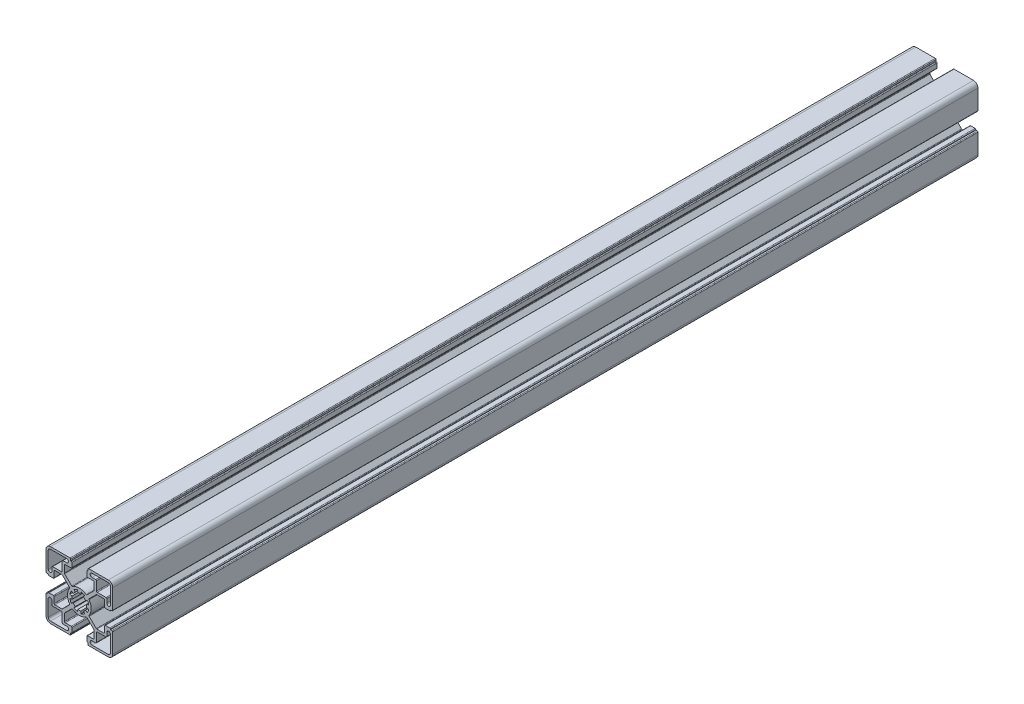
SolidWorks part; units mm, degrees
material "6063-O"
ref_plane "Front Plane" through (0, 0, 0) normal (0, 0, 1) x (1, 0, 0)
ref_plane "Top Plane" through (0, 0, 0) normal (0, 1, 0) x (1, 0, 0)
ref_plane "Right Plane" through (0, 0, 0) normal (1, 0, 0) x (0, 0, -1)
sketch "Sketch1" plane through (0, 0, 0) normal (0, 0, 1) x (1, 0, 0)
  line L0 (0, 22.5) -> (0, -22.5) construction
  line L1 (22.5, 0) -> (-22.5, 0) construction
  line L2 (-5.8, 22.5) -> (5.8, 22.5) construction
  line L3 (-5, 21) -> (5, 21) construction
  line L4 (-10.05, 10.05) -> (10.05, 10.05) construction
  line L5 (0, 0) -> (-10.05, 10.05) construction
  circle A0 centre (0, 0) radius 5 construction
  point P4 (0, 0)
  point P8 (0, 0)
  point P10 (0, 8)
  point P14 (0, 22.5)
  point P17 (0, 21)
  point P19 (0, 10.05)
sketch "Sketch2" plane through (0, 0, 0) normal (1, 0, 0) x (0, 0, -1)
  line L0 (152.4, 0) -> (-152.4, 0) construction
  point P4 (0, 0)
  dimension "D1" = 304.8
sketch "Sketch3" plane through (0, 0, 0) normal (0, 0, 1) x (1, 0, 0)
  line L5 (-21, 8.5375) -> (-21, 19.5)
  line L9 (0, 0) -> (-22.5, 22.5) construction
  line L10 (-11.55, -10.05) -> (-6.3569, -4.8569)
  line L11 (-19.5, 21) -> (-8.5375, 21)
  line L38 (-5.8, 22.5) -> (-5.8, 21)
  line L46 (-5.8, 21) -> (-5, 21)
  line L62 (-5, 21) -> (-5, 17.025)
  line L74 (-5, 17.025) -> (-10.05, 17.025)
  line L76 (-10.05, 17.025) -> (-10.05, 11.55)
  line L77 (-10.05, 11.55) -> (-4.8569, 6.3569)
  line L78 (-18.525, 8.5375) -> (-18.525, 11.55)
  line L79 (-10.05, 17.025) -> (-10.05, 22.5) construction
  line L80 (0, 22.5) -> (0, -22.5) construction
  line L81 (-5.8, 22.5) -> (5.8, 22.5) construction
  line L82 (10.05, 11.55) -> (4.8569, 6.3569)
  line L83 (10.05, 17.025) -> (10.05, 11.55)
  line L84 (5, 17.025) -> (10.05, 17.025)
  line L85 (5, 21) -> (5, 17.025)
  line L86 (5.8, 21) -> (5, 21)
  line L87 (5.8, 22.5) -> (5.8, 21)
  line L88 (-22.5, -5.8) -> (-21, -5.8)
  line L89 (-21, -5.8) -> (-21, -5)
  line L90 (-21, -5) -> (-17.025, -5)
  line L91 (-17.025, -5) -> (-17.025, -10.05)
  line L92 (-17.025, -10.05) -> (-11.55, -10.05)
  line L93 (-11.55, -10.05) -> (-6.3569, -4.8569)
  line L94 (-11.55, 10.05) -> (-6.3569, 4.8569)
  line L95 (-17.025, 10.05) -> (-11.55, 10.05)
  line L96 (-17.025, 5) -> (-17.025, 10.05)
  line L97 (-21, 5) -> (-17.025, 5)
  line L98 (-21, 5.8) -> (-21, 5)
  line L99 (-22.5, 5.8) -> (-21, 5.8)
  line L100 (-22.5, 5.8) -> (-22.5, 19.5)
  line L101 (-19.5, 22.5) -> (-5.8, 22.5)
  line L102 (-18.525, 11.55) -> (-11.55, 11.55)
  line L103 (-8.5375, 18.525) -> (-11.55, 18.525)
  line L104 (-11.55, 18.525) -> (-11.55, 11.55)
  line L108 (5.8, -22.5) -> (5.8, -21)
  line L113 (5.8, -21) -> (5, -21)
  line L117 (5.8, 22.5) -> (19.5, 22.5)
  line L118 (22.5, 19.5) -> (22.5, 5.8)
  line L119 (19.5, -22.5) -> (5.8, -22.5)
  line L120 (0, 0) -> (22.5, 0) construction
  line L121 (-22.5, -19.5) -> (-22.5, -5.8)
  line L136 (5, -21) -> (5, -17.025)
  line L137 (5, -17.025) -> (10.05, -17.025)
  line L138 (10.05, -17.025) -> (10.05, -11.55)
  line L139 (10.05, -11.55) -> (4.8569, -6.3569)
  line L140 (-10.05, -11.55) -> (-4.8569, -6.3569)
  line L141 (-10.05, -17.025) -> (-10.05, -11.55)
  line L142 (-5, -17.025) -> (-10.05, -17.025)
  line L143 (-5, -21) -> (-5, -17.025)
  line L144 (-5.8, -21) -> (-5, -21)
  line L145 (-5.8, -22.5) -> (-5.8, -21)
  line L146 (-5.8, -22.5) -> (-19.5, -22.5)
  line L147 (22.5, 5.8) -> (21, 5.8)
  line L148 (21, 5.8) -> (21, 5)
  line L149 (21, 5) -> (17.025, 5)
  line L150 (17.025, 5) -> (17.025, 10.05)
  line L151 (17.025, 10.05) -> (11.55, 10.05)
  line L152 (11.55, 10.05) -> (6.3569, 4.8569)
  line L153 (11.55, -10.05) -> (6.3569, -4.8569)
  line L154 (17.025, -10.05) -> (11.55, -10.05)
  line L155 (17.025, -5) -> (17.025, -10.05)
  line L156 (21, -5) -> (17.025, -5)
  line L157 (21, -5.8) -> (21, -5)
  line L158 (22.5, -5.8) -> (21, -5.8)
  line L159 (11.55, -10.05) -> (6.3569, -4.8569)
  line L160 (22.5, -5.8) -> (22.5, -19.5)
  line L161 (8.5375, 21) -> (19.5, 21)
  line L162 (21, 19.5) -> (21, 8.5375)
  line L163 (8.5375, 18.525) -> (11.55, 18.525)
  line L164 (11.55, 18.525) -> (11.55, 11.55)
  line L165 (18.525, 8.5375) -> (18.525, 11.55)
  line L166 (18.525, 11.55) -> (11.55, 11.55)
  line L167 (21, -8.5375) -> (21, -19.5)
  line L168 (19.5, -21) -> (8.5375, -21)
  line L169 (18.525, -8.5375) -> (18.525, -11.55)
  line L170 (18.525, -11.55) -> (11.55, -11.55)
  line L171 (8.5375, -18.525) -> (11.55, -18.525)
  line L172 (11.55, -18.525) -> (11.55, -11.55)
  line L173 (-8.5375, -21) -> (-19.5, -21)
  line L174 (-21, -19.5) -> (-21, -8.5375)
  line L175 (-8.5375, -18.525) -> (-11.55, -18.525)
  line L176 (-11.55, -18.525) -> (-11.55, -11.55)
  line L177 (-18.525, -8.5375) -> (-18.525, -11.55)
  line L178 (-18.525, -11.55) -> (-11.55, -11.55)
  line L179 (0, 0) -> (-11.55, 11.55) construction
  line L180 (0, 0) -> (11.55, 11.55) construction
  arc A2 (-21, 19.5) -> (-19.5, 21) centre (-19.5, 19.5) cw
  arc A73 (-4.8569, 6.3569) -> (4.8569, 6.3569) centre (0, 0) cw
  arc A74 (-6.3569, 4.8569) -> (-6.3569, -4.8569) centre (0, 0) ccw
  arc A75 (-19.5, 22.5) -> (-22.5, 19.5) centre (-19.5, 19.5) ccw
  arc A76 (-21, 8.5375) -> (-18.525, 8.5375) centre (-19.7625, 8.5375) ccw
  arc A77 (-8.5375, 21) -> (-8.5375, 18.525) centre (-8.5375, 19.7625) cw
  arc A80 (19.5, 22.5) -> (22.5, 19.5) centre (19.5, 19.5) cw
  arc A81 (22.5, -19.5) -> (19.5, -22.5) centre (19.5, -19.5) cw
  arc A82 (-19.5, -22.5) -> (-22.5, -19.5) centre (-19.5, -19.5) cw
  circle A88 centre (0, 0) radius 5 construction
  circle A89 centre (0, 0) radius 5
  arc A90 (-4.8569, -6.3569) -> (4.8569, -6.3569) centre (0, 0) ccw
  arc A91 (19.5, 21) -> (21, 19.5) centre (19.5, 19.5) cw
  arc A92 (6.3569, 4.8569) -> (6.3569, -4.8569) centre (0, 0) cw
  arc A93 (8.5375, 21) -> (8.5375, 18.525) centre (8.5375, 19.7625) ccw
  arc A94 (21, 8.5375) -> (18.525, 8.5375) centre (19.7625, 8.5375) cw
  arc A95 (21, -19.5) -> (19.5, -21) centre (19.5, -19.5) cw
  arc A96 (21, -8.5375) -> (18.525, -8.5375) centre (19.7625, -8.5375) ccw
  arc A97 (8.5375, -21) -> (8.5375, -18.525) centre (8.5375, -19.7625) cw
  arc A98 (-19.5, -21) -> (-21, -19.5) centre (-19.5, -19.5) cw
  arc A99 (-8.5375, -21) -> (-8.5375, -18.525) centre (-8.5375, -19.7625) ccw
  arc A100 (-21, -8.5375) -> (-18.525, -8.5375) centre (-19.7625, -8.5375) cw
  point P54 (-14.2875, 10.05)
  dimension "D2" = 3
  dimension "D3" = 1.5
  dimension "D4" = 1.5
  dimension "D5" = 1.5
  dimension "D6" = 90
  dimension "D1" = 4
extrude "Boss-Extrude1" add sketch "Sketch3" along normal up to vertex (152.4 mm away) and the other way up to vertex (152.4 mm away) contours A92 L152 L151 L150 L149 L148 L147 L118 A80 L117 L87 L86 L85 L84 L83 L82 A73 L77 L76 L74 L62 L46 L38 L101 A75 L100 L99 L98 L97 L96 L95 L94 A74 L10 L92 L91 L90 L89 L88 L121 A82 L146 L145 L144 L143 L142 L141 L140 A90 L139 L138 up to point (0, 0, 152.4) other way up to point (0, 0, -152.4)
fillet "Fillet1" radius 0.5 58 edges at (5, 21, 0) (5.8, 22.5, 0) (-5.8, 22.5, 0) (-5, 21, 0) (-10.05, 17.025, 0) (-5, 17.025, 0) (5, 17.025, 0) (-22.5, -5.8, 0) (-21, -5, 0) (-17.025, -5, 0) (-17.025, -10.05, 0) (-11.55, -10.05, 0) (-6.3569, -4.8569, 0) (-6.3569, 4.8569, 0) (-11.55, 10.05, 0) (-17.025, 10.05, 0) (-17.025, 5, 0) (-22.5, 5.8, 0) (-21, 5, 0) (-18.525, 11.55, 0) (-11.55, 11.55, 0) (-11.55, 18.525, 0) (4.8569, 6.3569, 0) (-4.8569, 6.3569, 0) (-10.05, 11.55, 0) (10.05, 17.025, 0) (10.05, 11.55, 0) (22.5, -5.8, 0) (21, -5, 0) (17.025, -5, 0) (17.025, -10.05, 0) (6.3569, 4.8569, 0) (11.55, 10.05, 0) (22.5, 5.8, 0) (21, 5, 0) (17.025, 5, 0) (4.8569, -6.3569, 0) (11.55, -11.55, 0) (-11.55, -11.55, 0) (18.525, -11.55, 0) (11.55, -18.525, 0) (10.05, -17.025, 0) (5, -17.025, 0) (5, -21, 0) (5.8, -22.5, 0) (-5.8, -22.5, 0) (-5, -21, 0) (-5, -17.025, 0) (-10.05, -17.025, 0) (-11.55, -18.525, 0) (11.55, 18.525, 0) (18.525, 11.55, 0) (11.55, 11.55, 0) (11.55, -10.05, 0) (6.3569, -4.8569, 0) (-4.8569, -6.3569, 0) (10.05, -11.55, 0) (-10.05, -11.55, 0)
sketch "Sketch4" plane through (0, 0, 152.4) normal (0, 0, 1) x (1, 0, 0)
  line L0 (-1.2681, 6.3751) -> (-0.9755, 4.9039)
  line L1 (0, 0) -> (0, 8) construction
  line L2 (-3.6112, 5.4046) -> (-2.7779, 4.1573)
  line L3 (1.2681, 6.3751) -> (0.9755, 4.9039)
  line L4 (3.6112, 5.4046) -> (2.7779, 4.1573)
  line L5 (5.4046, 3.6112) -> (4.1573, 2.7779)
  line L6 (6.3751, 1.2681) -> (4.9039, 0.9755)
  line L7 (6.3751, -1.2681) -> (4.9039, -0.9755)
  line L8 (5.4046, -3.6112) -> (4.1573, -2.7779)
  line L9 (3.6112, -5.4046) -> (2.7779, -4.1573)
  line L10 (1.2681, -6.3751) -> (0.9755, -4.9039)
  line L11 (-1.2681, -6.3751) -> (-0.9755, -4.9039)
  line L12 (-3.6112, -5.4046) -> (-2.7779, -4.1573)
  line L13 (-5.4046, -3.6112) -> (-4.1573, -2.7779)
  line L14 (-6.3751, -1.2681) -> (-4.9039, -0.9755)
  line L15 (-6.3751, 1.2681) -> (-4.9039, 0.9755)
  line L16 (-5.4046, 3.6112) -> (-4.1573, 2.7779)
  line L17 (0, 0) -> (-0.9755, 4.9039) construction
  line L18 (0, 0) -> (2.7779, 4.1573) construction
  arc A0 (-1.2681, 6.3751) -> (-3.6112, 5.4046) centre (0, 0) ccw
  circle A1 centre (0, 0) radius 5 construction
  arc A2 (-0.9755, 4.9039) -> (-2.7779, 4.1573) centre (0, 0) ccw
  arc A4 (2.7779, 4.1573) -> (0.9755, 4.9039) centre (0, 0) ccw
  arc A5 (3.6112, 5.4046) -> (1.2681, 6.3751) centre (0, 0) ccw
  arc A6 (4.9039, 0.9755) -> (4.1573, 2.7779) centre (0, 0) ccw
  arc A7 (6.3751, 1.2681) -> (5.4046, 3.6112) centre (0, 0) ccw
  arc A8 (4.1573, -2.7779) -> (4.9039, -0.9755) centre (0, 0) ccw
  arc A9 (5.4046, -3.6112) -> (6.3751, -1.2681) centre (0, 0) ccw
  arc A10 (0.9755, -4.9039) -> (2.7779, -4.1573) centre (0, 0) ccw
  arc A11 (1.2681, -6.3751) -> (3.6112, -5.4046) centre (0, 0) ccw
  arc A12 (-2.7779, -4.1573) -> (-0.9755, -4.9039) centre (0, 0) ccw
  arc A13 (-3.6112, -5.4046) -> (-1.2681, -6.3751) centre (0, 0) ccw
  arc A14 (-4.9039, -0.9755) -> (-4.1573, -2.7779) centre (0, 0) ccw
  arc A15 (-6.3751, -1.2681) -> (-5.4046, -3.6112) centre (0, 0) ccw
  arc A16 (-4.1573, 2.7779) -> (-4.9039, 0.9755) centre (0, 0) ccw
  arc A17 (-5.4046, 3.6112) -> (-6.3751, 1.2681) centre (0, 0) ccw
  dimension "D1" = 1.5
  dimension "D2" = 22.5
  dimension "D5" = 45
  dimension "D4" = 8
extrude "Cut-Extrude1" cut sketch "Sketch4" against normal through all
sketch "Sketch5" plane through (0, 0, 152.4) normal (0, 0, 1) x (1, 0, 0)
  line L6 (-11.55, -18.025) -> (-11.55, -12.05)
  line L7 (-8.5375, -18.525) -> (-11.05, -18.525)
  line L8 (-19.5, -21) -> (-8.5375, -21)
  line L9 (-21, -8.5375) -> (-21, -19.5)
  line L10 (-18.525, -11.55) -> (-18.525, -8.5375)
  line L11 (-12.05, -11.55) -> (-18.525, -11.55)
  line L12 (-11.55, -18.025) -> (-11.55, -12.05)
  line L13 (-8.5375, -18.525) -> (-11.05, -18.525)
  line L14 (-19.5, -21) -> (-8.5375, -21)
  line L15 (-21, -8.5375) -> (-21, -19.5)
  line L16 (-0.9755, 4.9039) -> (-1.2681, 6.3751)
  line L17 (1.2681, 6.3751) -> (0.9755, 4.9039)
  line L18 (2.7779, 4.1573) -> (3.6112, 5.4046)
  line L19 (5.4046, 3.6112) -> (4.1573, 2.7779)
  line L20 (4.9039, 0.9755) -> (6.3751, 1.2681)
  line L21 (6.3751, -1.2681) -> (4.9039, -0.9755)
  line L22 (4.1573, -2.7779) -> (5.4046, -3.6112)
  line L23 (3.6112, -5.4046) -> (2.7779, -4.1573)
  line L24 (0.9755, -4.9039) -> (1.2681, -6.3751)
  line L25 (-1.2681, -6.3751) -> (-0.9755, -4.9039)
  line L26 (-2.7779, -4.1573) -> (-3.6112, -5.4046)
  line L27 (-5.4046, -3.6112) -> (-4.1573, -2.7779)
  line L28 (-4.9039, -0.9755) -> (-6.3751, -1.2681)
  line L29 (-6.3751, 1.2681) -> (-4.9039, 0.9755)
  line L30 (-4.1573, 2.7779) -> (-5.4046, 3.6112)
  line L31 (-3.6112, 5.4046) -> (-2.7779, 4.1573)
  line L32 (-0.9755, 4.9039) -> (-1.2681, 6.3751)
  line L33 (1.2681, 6.3751) -> (0.9755, 4.9039)
  line L34 (2.7779, 4.1573) -> (3.6112, 5.4046)
  line L35 (5.4046, 3.6112) -> (4.1573, 2.7779)
  line L36 (4.9039, 0.9755) -> (6.3751, 1.2681)
  line L37 (6.3751, -1.2681) -> (4.9039, -0.9755)
  line L38 (4.1573, -2.7779) -> (5.4046, -3.6112)
  line L39 (3.6112, -5.4046) -> (2.7779, -4.1573)
  line L40 (0.9755, -4.9039) -> (1.2681, -6.3751)
  line L41 (-1.2681, -6.3751) -> (-0.9755, -4.9039)
  line L42 (-2.7779, -4.1573) -> (-3.6112, -5.4046)
  line L43 (-5.4046, -3.6112) -> (-4.1573, -2.7779)
  line L44 (-4.9039, -0.9755) -> (-6.3751, -1.2681)
  line L45 (-6.3751, 1.2681) -> (-4.9039, 0.9755)
  line L46 (-4.1573, 2.7779) -> (-5.4046, 3.6112)
  line L47 (-3.6112, 5.4046) -> (-2.7779, 4.1573)
  line L48 (-18.525, -11.55) -> (-18.525, -8.5375)
  line L49 (-12.05, -11.55) -> (-18.525, -11.55)
  line L50 (18.025, -11.55) -> (12.05, -11.55)
  line L51 (18.525, -8.5375) -> (18.525, -11.05)
  line L52 (21, -19.5) -> (21, -8.5375)
  line L53 (8.5375, -21) -> (19.5, -21)
  line L54 (11.05, -18.525) -> (8.5375, -18.525)
  line L55 (11.55, -12.05) -> (11.55, -18.025)
  line L56 (22.5, -19.5) -> (22.5, -6.3)
  line L57 (22, -5.8) -> (21, -5.8)
  line L58 (21, -5.8) -> (21, -5.5)
  line L59 (20.5, -5) -> (17.525, -5)
  line L60 (17.025, -5.5) -> (17.025, -9.55)
  line L61 (16.525, -10.05) -> (11.7571, -10.05)
  line L62 (11.4036, -9.9036) -> (6.6582, -5.1582)
  line L63 (6.6582, 5.1582) -> (11.4036, 9.9036)
  line L64 (11.7571, 10.05) -> (17.025, 10.05)
  line L65 (17.025, 10.05) -> (17.025, 5.5)
  line L66 (17.525, 5) -> (20.5, 5)
  line L67 (21, 5.5) -> (21, 5.8)
  line L68 (21, 5.8) -> (22, 5.8)
  line L69 (22.5, 6.3) -> (22.5, 19.5)
  line L70 (19.5, 22.5) -> (6.3, 22.5)
  line L71 (5.8, 22) -> (5.8, 21)
  line L72 (5.8, 21) -> (5.5, 21)
  line L73 (5, 20.5) -> (5, 17.525)
  line L74 (5.5, 17.025) -> (9.55, 17.025)
  line L75 (10.05, 16.525) -> (10.05, 11.7571)
  line L76 (9.9036, 11.4036) -> (5.1582, 6.6582)
  line L77 (-5.1582, 6.6582) -> (-9.9036, 11.4036)
  line L78 (-10.05, 11.7571) -> (-10.05, 16.525)
  line L79 (-9.55, 17.025) -> (-5.5, 17.025)
  line L80 (-5, 17.525) -> (-5, 20.5)
  line L81 (-5.5, 21) -> (-5.8, 21)
  line L82 (-5.8, 21) -> (-5.8, 22)
  line L83 (-6.3, 22.5) -> (-19.5, 22.5)
  line L84 (-22.5, 19.5) -> (-22.5, 6.3)
  line L85 (-22, 5.8) -> (-21, 5.8)
  line L86 (-21, 5.8) -> (-21, 5.5)
  line L87 (-20.5, 5) -> (-17.525, 5)
  line L88 (-17.025, 5.5) -> (-17.025, 9.55)
  line L89 (-16.525, 10.05) -> (-11.7571, 10.05)
  line L90 (-11.4036, 9.9036) -> (-6.6582, 5.1582)
  line L91 (-6.6582, -5.1582) -> (-11.4036, -9.9036)
  line L92 (-11.7571, -10.05) -> (-16.525, -10.05)
  line L93 (-17.025, -9.55) -> (-17.025, -5.5)
  line L94 (-17.525, -5) -> (-20.5, -5)
  line L95 (-21, -5.5) -> (-21, -5.8)
  line L96 (-21, -5.8) -> (-22, -5.8)
  line L97 (-22.5, -6.3) -> (-22.5, -19.5)
  line L98 (-19.5, -22.5) -> (-6.3, -22.5)
  line L99 (-5.8, -22) -> (-5.8, -21)
  line L100 (-5.8, -21) -> (-5.5, -21)
  line L101 (-5, -20.5) -> (-5, -17.525)
  line L102 (-5.5, -17.025) -> (-9.55, -17.025)
  line L103 (-10.05, -16.525) -> (-10.05, -11.7571)
  line L104 (-9.9036, -11.4036) -> (-5.1582, -6.6582)
  line L105 (5.1582, -6.6582) -> (9.9036, -11.4036)
  line L106 (10.05, -11.7571) -> (10.05, -16.525)
  line L107 (9.55, -17.025) -> (5.5, -17.025)
  line L108 (5, -17.525) -> (5, -20.5)
  line L109 (5.5, -21) -> (5.8, -21)
  line L110 (5.8, -21) -> (5.8, -22)
  line L111 (6.3, -22.5) -> (19.5, -22.5)
  line L112 (22.5, -19.5) -> (22.5, -6.3)
  line L113 (22, -5.8) -> (21, -5.8)
  line L114 (21, -5.8) -> (21, -5.5)
  line L115 (20.5, -5) -> (17.525, -5)
  line L116 (17.025, -5.5) -> (17.025, -9.55)
  line L117 (16.525, -10.05) -> (11.7571, -10.05)
  line L118 (11.4036, -9.9036) -> (6.6582, -5.1582)
  line L119 (6.6582, 5.1582) -> (11.4036, 9.9036)
  line L120 (11.7571, 10.05) -> (17.025, 10.05)
  line L121 (17.025, 10.05) -> (17.025, 5.5)
  line L122 (17.525, 5) -> (20.5, 5)
  line L123 (21, 5.5) -> (21, 5.8)
  line L124 (21, 5.8) -> (22, 5.8)
  line L125 (22.5, 6.3) -> (22.5, 19.5)
  line L126 (19.5, 22.5) -> (6.3, 22.5)
  line L127 (5.8, 22) -> (5.8, 21)
  line L128 (5.8, 21) -> (5.5, 21)
  line L129 (5, 20.5) -> (5, 17.525)
  line L130 (5.5, 17.025) -> (9.55, 17.025)
  line L131 (10.05, 16.525) -> (10.05, 11.7571)
  line L132 (9.9036, 11.4036) -> (5.1582, 6.6582)
  line L133 (-5.1582, 6.6582) -> (-9.9036, 11.4036)
  line L134 (-10.05, 11.7571) -> (-10.05, 16.525)
  line L135 (-9.55, 17.025) -> (-5.5, 17.025)
  line L136 (-5, 17.525) -> (-5, 20.5)
  line L137 (-5.5, 21) -> (-5.8, 21)
  line L138 (-5.8, 21) -> (-5.8, 22)
  line L139 (-6.3, 22.5) -> (-19.5, 22.5)
  line L140 (-22.5, 19.5) -> (-22.5, 6.3)
  line L141 (-22, 5.8) -> (-21, 5.8)
  line L142 (-21, 5.8) -> (-21, 5.5)
  line L143 (-20.5, 5) -> (-17.525, 5)
  line L144 (-17.025, 5.5) -> (-17.025, 9.55)
  line L145 (-16.525, 10.05) -> (-11.7571, 10.05)
  line L146 (-11.4036, 9.9036) -> (-6.6582, 5.1582)
  line L147 (-6.6582, -5.1582) -> (-11.4036, -9.9036)
  line L148 (-11.7571, -10.05) -> (-16.525, -10.05)
  line L149 (-17.025, -9.55) -> (-17.025, -5.5)
  line L150 (-17.525, -5) -> (-20.5, -5)
  line L151 (-21, -5.5) -> (-21, -5.8)
  line L152 (-21, -5.8) -> (-22, -5.8)
  line L153 (-22.5, -6.3) -> (-22.5, -19.5)
  line L154 (-19.5, -22.5) -> (-6.3, -22.5)
  line L155 (-5.8, -22) -> (-5.8, -21)
  line L156 (-5.8, -21) -> (-5.5, -21)
  line L157 (-5, -20.5) -> (-5, -17.525)
  line L158 (-5.5, -17.025) -> (-9.55, -17.025)
  line L159 (-10.05, -16.525) -> (-10.05, -11.7571)
  line L160 (-9.9036, -11.4036) -> (-5.1582, -6.6582)
  line L161 (5.1582, -6.6582) -> (9.9036, -11.4036)
  line L162 (10.05, -11.7571) -> (10.05, -16.525)
  line L163 (9.55, -17.025) -> (5.5, -17.025)
  line L164 (5, -17.525) -> (5, -20.5)
  line L165 (5.5, -21) -> (5.8, -21)
  line L166 (5.8, -21) -> (5.8, -22)
  line L167 (6.3, -22.5) -> (19.5, -22.5)
  line L168 (18.025, -11.55) -> (12.05, -11.55)
  line L169 (18.525, -8.5375) -> (18.525, -11.05)
  line L170 (21, -19.5) -> (21, -8.5375)
  line L171 (8.5375, -21) -> (19.5, -21)
  line L172 (11.05, -18.525) -> (8.5375, -18.525)
  line L173 (11.55, -12.05) -> (11.55, -18.025)
  line L174 (11.55, 18.025) -> (11.55, 12.05)
  line L175 (8.5375, 18.525) -> (11.05, 18.525)
  line L176 (19.5, 21) -> (8.5375, 21)
  line L177 (21, 8.5375) -> (21, 19.5)
  line L178 (18.525, 11.05) -> (18.525, 8.5375)
  line L179 (12.05, 11.55) -> (18.025, 11.55)
  line L180 (11.55, 18.025) -> (11.55, 12.05)
  line L181 (8.5375, 18.525) -> (11.05, 18.525)
  line L182 (19.5, 21) -> (8.5375, 21)
  line L183 (21, 8.5375) -> (21, 19.5)
  line L184 (18.525, 11.05) -> (18.525, 8.5375)
  line L185 (12.05, 11.55) -> (18.025, 11.55)
  line L186 (-18.025, 11.55) -> (-12.05, 11.55)
  line L187 (-18.525, 8.5375) -> (-18.525, 11.05)
  line L188 (-21, 19.5) -> (-21, 8.5375)
  line L189 (-8.5375, 21) -> (-19.5, 21)
  line L190 (-11.05, 18.525) -> (-8.5375, 18.525)
  line L191 (-11.55, 12.05) -> (-11.55, 18.025)
  line L192 (-18.025, 11.55) -> (-12.05, 11.55)
  line L193 (-18.525, 8.5375) -> (-18.525, 11.05)
  line L194 (-21, 19.5) -> (-21, 8.5375)
  line L195 (-8.5375, 21) -> (-19.5, 21)
  line L196 (-11.05, 18.525) -> (-8.5375, 18.525)
  line L197 (-11.55, 12.05) -> (-11.55, 18.025)
  arc A5 (-11.55, -18.025) -> (-11.05, -18.525) centre (-11.05, -18.025) ccw
  arc A6 (-8.5375, -21) -> (-8.5375, -18.525) centre (-8.5375, -19.7625) ccw
  arc A7 (-21, -19.5) -> (-19.5, -21) centre (-19.5, -19.5) ccw
  arc A8 (-18.525, -8.5375) -> (-21, -8.5375) centre (-19.7625, -8.5375) ccw
  arc A9 (-11.55, -12.05) -> (-12.05, -11.55) centre (-12.05, -12.05) ccw
  arc A10 (-11.55, -18.025) -> (-11.05, -18.525) centre (-11.05, -18.025) ccw
  arc A11 (-8.5375, -21) -> (-8.5375, -18.525) centre (-8.5375, -19.7625) ccw
  arc A12 (-21, -19.5) -> (-19.5, -21) centre (-19.5, -19.5) ccw
  arc A13 (-18.525, -8.5375) -> (-21, -8.5375) centre (-19.7625, -8.5375) ccw
  arc A14 (-11.55, -12.05) -> (-12.05, -11.55) centre (-12.05, -12.05) ccw
  arc A16 (0.9755, 4.9039) -> (-0.9755, 4.9039) centre (0, 0) ccw
  arc A17 (3.6112, 5.4046) -> (1.2681, 6.3751) centre (0, 0) ccw
  arc A18 (4.1573, 2.7779) -> (2.7779, 4.1573) centre (0, 0) ccw
  arc A19 (6.3751, 1.2681) -> (5.4046, 3.6112) centre (0, 0) ccw
  arc A20 (4.9039, -0.9755) -> (4.9039, 0.9755) centre (0, 0) ccw
  arc A21 (5.4046, -3.6112) -> (6.3751, -1.2681) centre (0, 0) ccw
  arc A22 (2.7779, -4.1573) -> (4.1573, -2.7779) centre (0, 0) ccw
  arc A23 (1.2681, -6.3751) -> (3.6112, -5.4046) centre (0, 0) ccw
  arc A24 (-0.9755, -4.9039) -> (0.9755, -4.9039) centre (0, 0) ccw
  arc A25 (-3.6112, -5.4046) -> (-1.2681, -6.3751) centre (0, 0) ccw
  arc A26 (-4.1573, -2.7779) -> (-2.7779, -4.1573) centre (0, 0) ccw
  arc A27 (-6.3751, -1.2681) -> (-5.4046, -3.6112) centre (0, 0) ccw
  arc A28 (-4.9039, 0.9755) -> (-4.9039, -0.9755) centre (0, 0) ccw
  arc A29 (-5.4046, 3.6112) -> (-6.3751, 1.2681) centre (0, 0) ccw
  arc A30 (-2.7779, 4.1573) -> (-4.1573, 2.7779) centre (0, 0) ccw
  arc A31 (-1.2681, 6.3751) -> (-3.6112, 5.4046) centre (0, 0) ccw
  arc A32 (0.9755, 4.9039) -> (-0.9755, 4.9039) centre (0, 0) ccw
  arc A33 (3.6112, 5.4046) -> (1.2681, 6.3751) centre (0, 0) ccw
  arc A34 (4.1573, 2.7779) -> (2.7779, 4.1573) centre (0, 0) ccw
  arc A35 (6.3751, 1.2681) -> (5.4046, 3.6112) centre (0, 0) ccw
  arc A36 (4.9039, -0.9755) -> (4.9039, 0.9755) centre (0, 0) ccw
  arc A37 (5.4046, -3.6112) -> (6.3751, -1.2681) centre (0, 0) ccw
  arc A38 (2.7779, -4.1573) -> (4.1573, -2.7779) centre (0, 0) ccw
  arc A39 (1.2681, -6.3751) -> (3.6112, -5.4046) centre (0, 0) ccw
  arc A40 (-0.9755, -4.9039) -> (0.9755, -4.9039) centre (0, 0) ccw
  arc A41 (-3.6112, -5.4046) -> (-1.2681, -6.3751) centre (0, 0) ccw
  arc A42 (-4.1573, -2.7779) -> (-2.7779, -4.1573) centre (0, 0) ccw
  arc A43 (-6.3751, -1.2681) -> (-5.4046, -3.6112) centre (0, 0) ccw
  arc A44 (-4.9039, 0.9755) -> (-4.9039, -0.9755) centre (0, 0) ccw
  arc A45 (-5.4046, 3.6112) -> (-6.3751, 1.2681) centre (0, 0) ccw
  arc A46 (-2.7779, 4.1573) -> (-4.1573, 2.7779) centre (0, 0) ccw
  arc A47 (-1.2681, 6.3751) -> (-3.6112, 5.4046) centre (0, 0) ccw
  arc A48 (18.025, -11.55) -> (18.525, -11.05) centre (18.025, -11.05) ccw
  arc A49 (21, -8.5375) -> (18.525, -8.5375) centre (19.7625, -8.5375) ccw
  arc A50 (19.5, -21) -> (21, -19.5) centre (19.5, -19.5) ccw
  arc A51 (8.5375, -18.525) -> (8.5375, -21) centre (8.5375, -19.7625) ccw
  arc A52 (11.05, -18.525) -> (11.55, -18.025) centre (11.05, -18.025) ccw
  arc A53 (12.05, -11.55) -> (11.55, -12.05) centre (12.05, -12.05) ccw
  arc A54 (18.025, -11.55) -> (18.525, -11.05) centre (18.025, -11.05) ccw
  arc A55 (22.5, -6.3) -> (22, -5.8) centre (22, -6.3) ccw
  arc A56 (21, -5.5) -> (20.5, -5) centre (20.5, -5.5) ccw
  arc A57 (17.525, -5) -> (17.025, -5.5) centre (17.525, -5.5) ccw
  arc A58 (16.525, -10.05) -> (17.025, -9.55) centre (16.525, -9.55) ccw
  arc A59 (11.4036, -9.9036) -> (11.7571, -10.05) centre (11.7571, -9.55) ccw
  arc A60 (6.5993, -4.522) -> (6.6582, -5.1582) centre (7.0118, -4.8047) ccw
  arc A61 (6.5993, -4.522) -> (6.5993, 4.522) centre (0, 0) ccw
  arc A62 (6.6582, 5.1582) -> (6.5993, 4.522) centre (7.0118, 4.8047) ccw
  arc A63 (11.7571, 10.05) -> (11.4036, 9.9036) centre (11.7571, 9.55) ccw
  arc A64 (17.025, 5.5) -> (17.525, 5) centre (17.525, 5.5) ccw
  arc A65 (20.5, 5) -> (21, 5.5) centre (20.5, 5.5) ccw
  arc A66 (22, 5.8) -> (22.5, 6.3) centre (22, 6.3) ccw
  arc A67 (22.5, 19.5) -> (19.5, 22.5) centre (19.5, 19.5) ccw
  arc A68 (6.3, 22.5) -> (5.8, 22) centre (6.3, 22) ccw
  arc A69 (5.5, 21) -> (5, 20.5) centre (5.5, 20.5) ccw
  arc A70 (5, 17.525) -> (5.5, 17.025) centre (5.5, 17.525) ccw
  arc A71 (10.05, 16.525) -> (9.55, 17.025) centre (9.55, 16.525) ccw
  arc A72 (9.9036, 11.4036) -> (10.05, 11.7571) centre (9.55, 11.7571) ccw
  arc A73 (4.522, 6.5993) -> (5.1582, 6.6582) centre (4.8047, 7.0118) ccw
  arc A74 (4.522, 6.5993) -> (-4.522, 6.5993) centre (0, 0) ccw
  arc A75 (-5.1582, 6.6582) -> (-4.522, 6.5993) centre (-4.8047, 7.0118) ccw
  arc A76 (-10.05, 11.7571) -> (-9.9036, 11.4036) centre (-9.55, 11.7571) ccw
  arc A77 (-9.55, 17.025) -> (-10.05, 16.525) centre (-9.55, 16.525) ccw
  arc A78 (-5.5, 17.025) -> (-5, 17.525) centre (-5.5, 17.525) ccw
  arc A79 (-5, 20.5) -> (-5.5, 21) centre (-5.5, 20.5) ccw
  arc A80 (-5.8, 22) -> (-6.3, 22.5) centre (-6.3, 22) ccw
  arc A81 (-19.5, 22.5) -> (-22.5, 19.5) centre (-19.5, 19.5) ccw
  arc A82 (-22.5, 6.3) -> (-22, 5.8) centre (-22, 6.3) ccw
  arc A83 (-21, 5.5) -> (-20.5, 5) centre (-20.5, 5.5) ccw
  arc A84 (-17.525, 5) -> (-17.025, 5.5) centre (-17.525, 5.5) ccw
  arc A85 (-16.525, 10.05) -> (-17.025, 9.55) centre (-16.525, 9.55) ccw
  arc A86 (-11.4036, 9.9036) -> (-11.7571, 10.05) centre (-11.7571, 9.55) ccw
  arc A87 (-6.5993, 4.522) -> (-6.6582, 5.1582) centre (-7.0118, 4.8047) ccw
  arc A88 (-6.5993, 4.522) -> (-6.5993, -4.522) centre (0, 0) ccw
  arc A89 (-6.6582, -5.1582) -> (-6.5993, -4.522) centre (-7.0118, -4.8047) ccw
  arc A90 (-11.7571, -10.05) -> (-11.4036, -9.9036) centre (-11.7571, -9.55) ccw
  arc A91 (-17.025, -9.55) -> (-16.525, -10.05) centre (-16.525, -9.55) ccw
  arc A92 (-17.025, -5.5) -> (-17.525, -5) centre (-17.525, -5.5) ccw
  arc A93 (-20.5, -5) -> (-21, -5.5) centre (-20.5, -5.5) ccw
  arc A94 (-22, -5.8) -> (-22.5, -6.3) centre (-22, -6.3) ccw
  arc A95 (-22.5, -19.5) -> (-19.5, -22.5) centre (-19.5, -19.5) ccw
  arc A96 (-6.3, -22.5) -> (-5.8, -22) centre (-6.3, -22) ccw
  arc A97 (-5.5, -21) -> (-5, -20.5) centre (-5.5, -20.5) ccw
  arc A98 (-5, -17.525) -> (-5.5, -17.025) centre (-5.5, -17.525) ccw
  arc A99 (-10.05, -16.525) -> (-9.55, -17.025) centre (-9.55, -16.525) ccw
  arc A100 (-9.9036, -11.4036) -> (-10.05, -11.7571) centre (-9.55, -11.7571) ccw
  arc A101 (-4.522, -6.5993) -> (-5.1582, -6.6582) centre (-4.8047, -7.0118) ccw
  arc A102 (-4.522, -6.5993) -> (4.522, -6.5993) centre (0, 0) ccw
  arc A103 (5.1582, -6.6582) -> (4.522, -6.5993) centre (4.8047, -7.0118) ccw
  arc A104 (10.05, -11.7571) -> (9.9036, -11.4036) centre (9.55, -11.7571) ccw
  arc A105 (9.55, -17.025) -> (10.05, -16.525) centre (9.55, -16.525) ccw
  arc A106 (5.5, -17.025) -> (5, -17.525) centre (5.5, -17.525) ccw
  arc A107 (5, -20.5) -> (5.5, -21) centre (5.5, -20.5) ccw
  arc A108 (5.8, -22) -> (6.3, -22.5) centre (6.3, -22) ccw
  arc A109 (19.5, -22.5) -> (22.5, -19.5) centre (19.5, -19.5) ccw
  arc A110 (22.5, -6.3) -> (22, -5.8) centre (22, -6.3) ccw
  arc A111 (21, -5.5) -> (20.5, -5) centre (20.5, -5.5) ccw
  arc A112 (17.525, -5) -> (17.025, -5.5) centre (17.525, -5.5) ccw
  arc A113 (16.525, -10.05) -> (17.025, -9.55) centre (16.525, -9.55) ccw
  arc A114 (11.4036, -9.9036) -> (11.7571, -10.05) centre (11.7571, -9.55) ccw
  arc A115 (6.5993, -4.522) -> (6.6582, -5.1582) centre (7.0118, -4.8047) ccw
  arc A116 (6.5993, -4.522) -> (6.5993, 4.522) centre (0, 0) ccw
  arc A117 (6.6582, 5.1582) -> (6.5993, 4.522) centre (7.0118, 4.8047) ccw
  arc A118 (11.7571, 10.05) -> (11.4036, 9.9036) centre (11.7571, 9.55) ccw
  arc A119 (17.025, 5.5) -> (17.525, 5) centre (17.525, 5.5) ccw
  arc A120 (20.5, 5) -> (21, 5.5) centre (20.5, 5.5) ccw
  arc A121 (22, 5.8) -> (22.5, 6.3) centre (22, 6.3) ccw
  arc A122 (22.5, 19.5) -> (19.5, 22.5) centre (19.5, 19.5) ccw
  arc A123 (6.3, 22.5) -> (5.8, 22) centre (6.3, 22) ccw
  arc A124 (5.5, 21) -> (5, 20.5) centre (5.5, 20.5) ccw
  arc A125 (5, 17.525) -> (5.5, 17.025) centre (5.5, 17.525) ccw
  arc A126 (10.05, 16.525) -> (9.55, 17.025) centre (9.55, 16.525) ccw
  arc A127 (9.9036, 11.4036) -> (10.05, 11.7571) centre (9.55, 11.7571) ccw
  arc A128 (4.522, 6.5993) -> (5.1582, 6.6582) centre (4.8047, 7.0118) ccw
  arc A129 (4.522, 6.5993) -> (-4.522, 6.5993) centre (0, 0) ccw
  arc A130 (-5.1582, 6.6582) -> (-4.522, 6.5993) centre (-4.8047, 7.0118) ccw
  arc A131 (-10.05, 11.7571) -> (-9.9036, 11.4036) centre (-9.55, 11.7571) ccw
  arc A132 (-9.55, 17.025) -> (-10.05, 16.525) centre (-9.55, 16.525) ccw
  arc A133 (-5.5, 17.025) -> (-5, 17.525) centre (-5.5, 17.525) ccw
  arc A134 (-5, 20.5) -> (-5.5, 21) centre (-5.5, 20.5) ccw
  arc A135 (-5.8, 22) -> (-6.3, 22.5) centre (-6.3, 22) ccw
  arc A136 (-19.5, 22.5) -> (-22.5, 19.5) centre (-19.5, 19.5) ccw
  arc A137 (-22.5, 6.3) -> (-22, 5.8) centre (-22, 6.3) ccw
  arc A138 (-21, 5.5) -> (-20.5, 5) centre (-20.5, 5.5) ccw
  arc A139 (-17.525, 5) -> (-17.025, 5.5) centre (-17.525, 5.5) ccw
  arc A140 (-16.525, 10.05) -> (-17.025, 9.55) centre (-16.525, 9.55) ccw
  arc A141 (-11.4036, 9.9036) -> (-11.7571, 10.05) centre (-11.7571, 9.55) ccw
  arc A142 (-6.5993, 4.522) -> (-6.6582, 5.1582) centre (-7.0118, 4.8047) ccw
  arc A143 (-6.5993, 4.522) -> (-6.5993, -4.522) centre (0, 0) ccw
  arc A144 (-6.6582, -5.1582) -> (-6.5993, -4.522) centre (-7.0118, -4.8047) ccw
  arc A145 (-11.7571, -10.05) -> (-11.4036, -9.9036) centre (-11.7571, -9.55) ccw
  arc A146 (-17.025, -9.55) -> (-16.525, -10.05) centre (-16.525, -9.55) ccw
  arc A147 (-17.025, -5.5) -> (-17.525, -5) centre (-17.525, -5.5) ccw
  arc A148 (-20.5, -5) -> (-21, -5.5) centre (-20.5, -5.5) ccw
  arc A149 (-22, -5.8) -> (-22.5, -6.3) centre (-22, -6.3) ccw
  arc A150 (-22.5, -19.5) -> (-19.5, -22.5) centre (-19.5, -19.5) ccw
  arc A151 (-6.3, -22.5) -> (-5.8, -22) centre (-6.3, -22) ccw
  arc A152 (-5.5, -21) -> (-5, -20.5) centre (-5.5, -20.5) ccw
  arc A153 (-5, -17.525) -> (-5.5, -17.025) centre (-5.5, -17.525) ccw
  arc A154 (-10.05, -16.525) -> (-9.55, -17.025) centre (-9.55, -16.525) ccw
  arc A155 (-9.9036, -11.4036) -> (-10.05, -11.7571) centre (-9.55, -11.7571) ccw
  arc A156 (-4.522, -6.5993) -> (-5.1582, -6.6582) centre (-4.8047, -7.0118) ccw
  arc A157 (-4.522, -6.5993) -> (4.522, -6.5993) centre (0, 0) ccw
  arc A158 (5.1582, -6.6582) -> (4.522, -6.5993) centre (4.8047, -7.0118) ccw
  arc A159 (10.05, -11.7571) -> (9.9036, -11.4036) centre (9.55, -11.7571) ccw
  arc A160 (9.55, -17.025) -> (10.05, -16.525) centre (9.55, -16.525) ccw
  arc A161 (5.5, -17.025) -> (5, -17.525) centre (5.5, -17.525) ccw
  arc A162 (5, -20.5) -> (5.5, -21) centre (5.5, -20.5) ccw
  arc A163 (5.8, -22) -> (6.3, -22.5) centre (6.3, -22) ccw
  arc A164 (19.5, -22.5) -> (22.5, -19.5) centre (19.5, -19.5) ccw
  arc A165 (21, -8.5375) -> (18.525, -8.5375) centre (19.7625, -8.5375) ccw
  arc A166 (19.5, -21) -> (21, -19.5) centre (19.5, -19.5) ccw
  arc A167 (8.5375, -18.525) -> (8.5375, -21) centre (8.5375, -19.7625) ccw
  arc A168 (11.05, -18.525) -> (11.55, -18.025) centre (11.05, -18.025) ccw
  arc A169 (12.05, -11.55) -> (11.55, -12.05) centre (12.05, -12.05) ccw
  arc A170 (11.55, 18.025) -> (11.05, 18.525) centre (11.05, 18.025) ccw
  arc A171 (8.5375, 21) -> (8.5375, 18.525) centre (8.5375, 19.7625) ccw
  arc A172 (21, 19.5) -> (19.5, 21) centre (19.5, 19.5) ccw
  arc A173 (18.525, 8.5375) -> (21, 8.5375) centre (19.7625, 8.5375) ccw
  arc A174 (18.525, 11.05) -> (18.025, 11.55) centre (18.025, 11.05) ccw
  arc A175 (11.55, 12.05) -> (12.05, 11.55) centre (12.05, 12.05) ccw
  arc A176 (11.55, 18.025) -> (11.05, 18.525) centre (11.05, 18.025) ccw
  arc A177 (8.5375, 21) -> (8.5375, 18.525) centre (8.5375, 19.7625) ccw
  arc A178 (21, 19.5) -> (19.5, 21) centre (19.5, 19.5) ccw
  arc A179 (18.525, 8.5375) -> (21, 8.5375) centre (19.7625, 8.5375) ccw
  arc A180 (18.525, 11.05) -> (18.025, 11.55) centre (18.025, 11.05) ccw
  arc A181 (11.55, 12.05) -> (12.05, 11.55) centre (12.05, 12.05) ccw
  arc A182 (-18.025, 11.55) -> (-18.525, 11.05) centre (-18.025, 11.05) ccw
  arc A183 (-21, 8.5375) -> (-18.525, 8.5375) centre (-19.7625, 8.5375) ccw
  arc A184 (-19.5, 21) -> (-21, 19.5) centre (-19.5, 19.5) ccw
  arc A185 (-8.5375, 18.525) -> (-8.5375, 21) centre (-8.5375, 19.7625) ccw
  arc A186 (-11.05, 18.525) -> (-11.55, 18.025) centre (-11.05, 18.025) ccw
  arc A187 (-12.05, 11.55) -> (-11.55, 12.05) centre (-12.05, 12.05) ccw
  arc A188 (-18.025, 11.55) -> (-18.525, 11.05) centre (-18.025, 11.05) ccw
  arc A189 (-21, 8.5375) -> (-18.525, 8.5375) centre (-19.7625, 8.5375) ccw
  arc A190 (-19.5, 21) -> (-21, 19.5) centre (-19.5, 19.5) ccw
  arc A191 (-8.5375, 18.525) -> (-8.5375, 21) centre (-8.5375, 19.7625) ccw
  arc A192 (-11.05, 18.525) -> (-11.55, 18.025) centre (-11.05, 18.025) ccw
  arc A193 (-12.05, 11.55) -> (-11.55, 12.05) centre (-12.05, 12.05) ccw
  dimension "D1" = 0
  dimension "D2" = 0
  dimension "D3" = 0
  dimension "D4" = 0
  dimension "D5" = 0
  dimension "D6" = 0
extrude "Boss-Extrude2" add sketch "Sketch5" along normal blind 279.1
equation "\"D3@Sketch3\"=\"Wall@Sketch1\""
equation "\"D4@Sketch3\"=\"Wall@Sketch1\""
equation "\"D5@Sketch3\"=\"Wall@Sketch1\""
equation "\"D1@Sketch4\"=\"Wall@Sketch1\""
